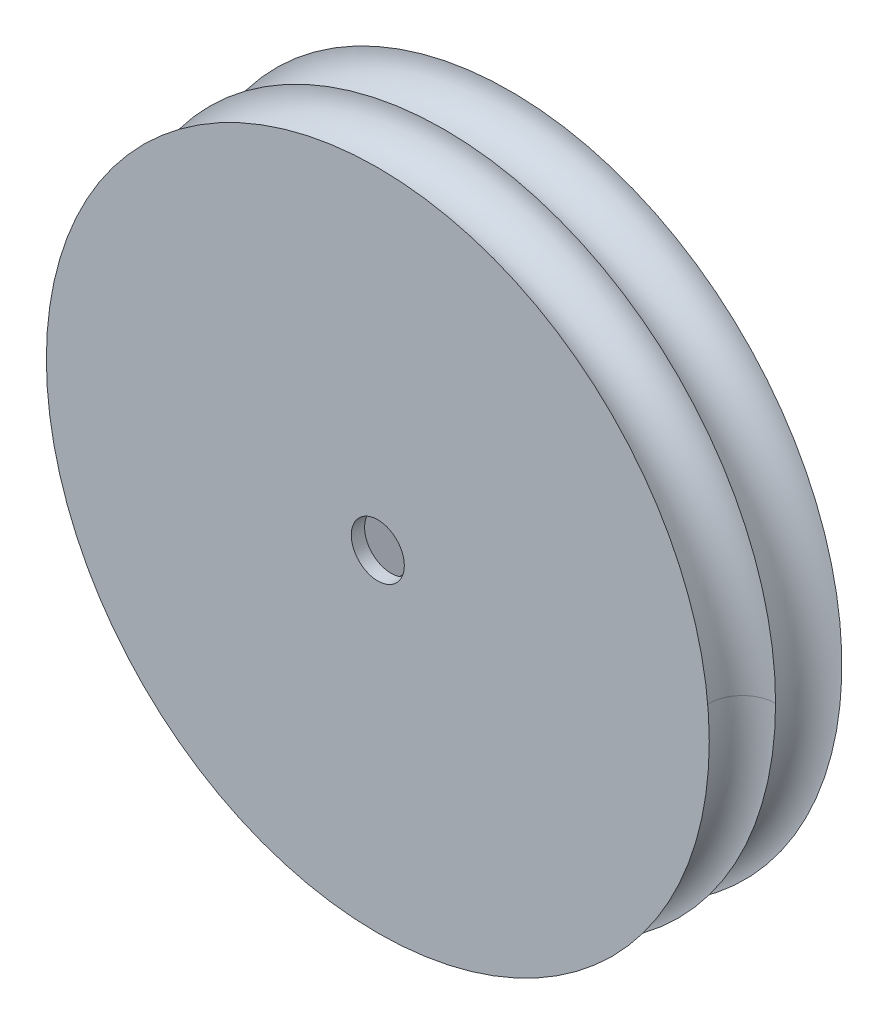
SolidWorks part; units mm, degrees
material "PC 高粘度"
ref_plane "前视基准面" through (0, 0, 0) normal (0, 0, 1) x (1, 0, 0)
ref_plane "上视基准面" through (0, 0, 0) normal (0, 1, 0) x (1, 0, 0)
ref_plane "右视基准面" through (0, 0, 0) normal (1, 0, 0) x (0, 0, -1)
sketch "草图1" plane through (0, 0, 0) normal (0, 0, 1) x (1, 0, 0)
  line L1 (3.4641, 6) -> (-3.4641, 6)
  line L2 (-3.4641, 6) -> (-6.9282, 0)
  line L3 (-6.9282, 0) -> (-3.4641, -6)
  line L4 (-3.4641, -6) -> (3.4641, -6)
  line L5 (3.4641, -6) -> (6.9282, 0)
  line L6 (6.9282, 0) -> (3.4641, 6)
  circle A2 centre (0, 0) radius 25
extrude "凸台-拉伸1" add sketch "草图1" along normal blind 4 from offset 1
sketch "草图4" plane through (0, 0, 5) normal (0, 0, 1) x (1, 0, 0)
  circle A0 centre (0, 0) radius 25
  circle A1 centre (0, 0) radius 2
extrude "凸台-拉伸3" add sketch "草图4" along normal blind 1
sketch "草图6" plane through (0, 0, 0) normal (0, 1, 0) x (1, 0, 0)
  circle A0 centre (-25, -3.5) radius 2.5
sweep "切除-扫描1" cut profiles "草图6" path edge at (25, 0, 1)
sketch "草图8" plane through (0, 0, 1) normal (0, 0, -1) x (-1, 0, 0)
  circle A0 centre (0, 0) radius 25
  circle A1 centre (0, 0) radius 19
extrude "凸台-拉伸4" add sketch "草图8" along normal blind 5
sketch "草图11" plane through (0, 0, 1) normal (0, 0, -1) x (-1, 0, 0)
  line L0 (-3.4641, 6) -> (-6.9282, 0)
  line L1 (-6.9282, 0) -> (-3.4641, -6)
  line L2 (-3.4641, -6) -> (3.4641, -6)
  line L3 (3.4641, -6) -> (6.9282, 0)
  line L4 (6.9282, 0) -> (3.4641, 6)
  line L5 (3.4641, 6) -> (-3.4641, 6)
  circle A0 centre (0, 0) radius 9
extrude "凸台-拉伸6" add sketch "草图11" along normal blind 2
sketch "草图12" plane through (0, 0, 0) normal (0, 1, 0) x (1, 0, 0)
  line L1 (19, 4) -> (19, -1)
  line L2 (19, -1) -> (9, -1)
  line L3 (9, -1) -> (9, 1)
  line L4 (0, 23.4186) -> (0, -34.8261) construction
  line L5 (9.3921, 1) -> (9, 1)
  line L6 (15.9782, 2.5232) -> (19, 4)
  arc A0 (15.9782, 2.5232) -> (9.3921, 1) centre (9.3921, 16) cw
  dimension "D1" = 15
revolve "旋转1" add sketch "草图12" angle 15 about L4
pattern_circular "阵列(圆周)1" count 5 over 360 about axis through (0, 0, 0) along (0, 0, 1) of "旋转1"
sketch "草图13" plane through (0, 0, 0) normal (0, 1, 0) x (1, 0, 0)
  line L0 (-25, 4) -> (-25, -1) construction
  circle A0 centre (-25, 1.5) radius 2.5
sweep "切除-扫描2" cut profiles "草图13" path edge at (-25, 0, -4)
